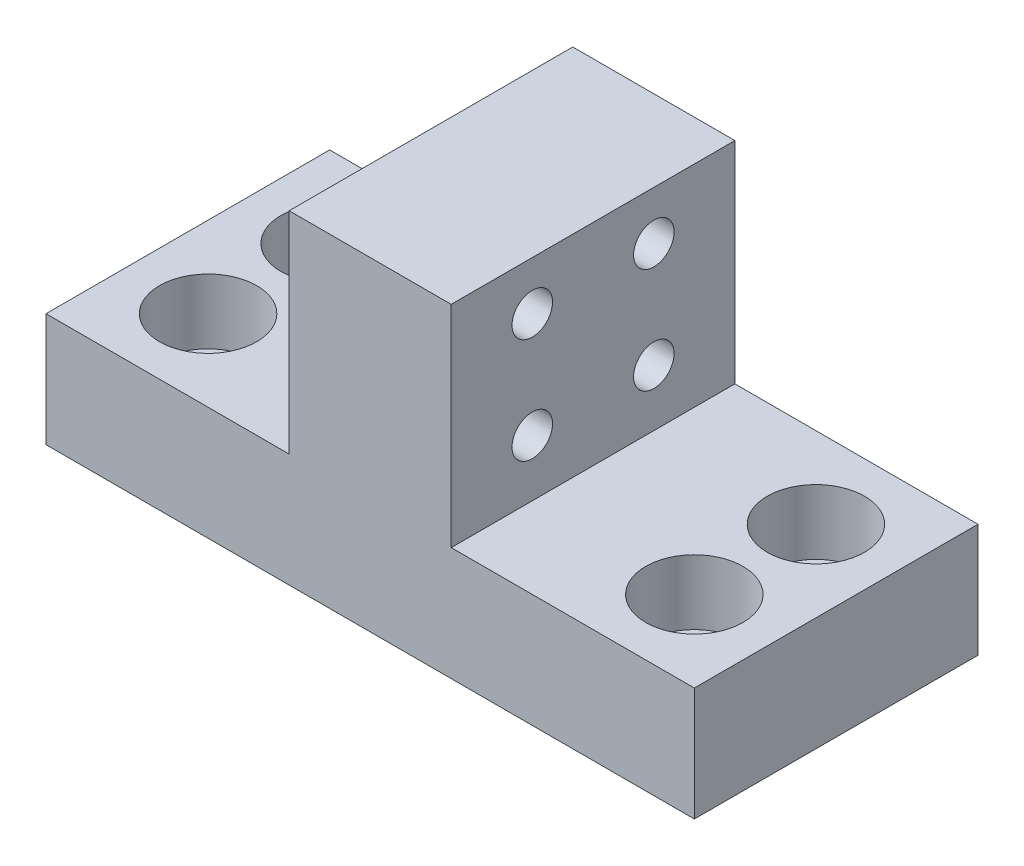
SolidWorks part; units mm, degrees
ref_plane "前视基准面" through (0, 0, 0) normal (0, 0, 1) x (1, 0, 0)
ref_plane "上视基准面" through (0, 0, 0) normal (0, 1, 0) x (1, 0, 0)
ref_plane "右视基准面" through (0, 0, 0) normal (1, 0, 0) x (0, 0, -1)
sketch "草图1" plane through (0, 0, 0) normal (0, 1, 0) x (1, 0, 0)
  line L0 (-40, 17.5) -> (-40, -17.5)
  line L1 (-40, -17.5) -> (40, -17.5)
  line L2 (40, -17.5) -> (40, 17.5)
  line L3 (40, 17.5) -> (-40, 17.5)
  line L4 (0, 0) -> (80, 0) construction
  line L5 (0, 0) -> (0, 15.8626) construction
  point P10 (0, 17.5)
  point P12 (40, 0)
  dimension "D1" = 35
  dimension "D2" = 80
extrude "凸台-拉伸1" add sketch "草图1" along normal blind 14
sketch "草图2" plane through (0, 14, 0) normal (0, 1, 0) x (1, 0, 0)
  line L0 (0, 0) -> (0, 23.1433) construction
  line L1 (0, 0) -> (16.8315, 0) construction
  line L2 (-10, 17.5) -> (-10, -17.5)
  line L3 (40, 17.5) -> (-40, 17.5) construction
  line L4 (-40, -17.5) -> (40, -17.5) construction
  line L5 (10, -17.5) -> (10, 17.5)
  line L6 (10, 17.5) -> (-10, 17.5)
  line L7 (10, -17.5) -> (-10, -17.5)
  point P12 (0, 17.5)
  dimension "D1" = 20
extrude "凸台-拉伸2" add sketch "草图2" along normal blind 26
hole_wizard "M20 六角头螺栓的柱形沉头孔1" positions "草图3" profile "草图4" counterbore size "M20" standard "GB" end condition up to next
sketch "草图3" plane through (0, 14, 0) normal (0, 1, 0) x (1, 0, 0)
  line L0 (-10, 17.5) -> (-40, 17.5) construction
  point P0 (-30, 7.5)
  dimension "D1" = 10
  dimension "D2" = 30
sketch "草图4" plane through (-30, 14, -7.5) normal (1, 0, 0) x (0, 0, 1)
  line L0 (0, 0) -> (0, 14.001)
  line L1 (0, 14.001) -> (3.5, 14.001)
  line L3 (3.5, 14.001) -> (3.5, 8)
  line L4 (3.5, 8) -> (6, 8)
  line L5 (6, 8) -> (6, 0)
  line L7 (6, 0) -> (0, 0)
  line L11 (0, -6.35) -> (0, 107.95) construction
  dimension "通孔孔直径" = 7
  dimension "通孔孔深度" = 14.001
  dimension "柱形沉头孔直径" = 12
  dimension "柱形沉头孔深度" = 8
pattern_linear "阵列(线性)1" count 2 spacing 60 along (1, 0, 0) count 2 spacing 15 along (0, 0, 1) of "M20 六角头螺栓的柱形沉头孔1"
sketch "草图5" plane through (-10, 0, 0) normal (-1, 0, 0) x (0, 0, 1)
  line L0 (-17.5, 0) -> (17.5, 0) construction
  circle A0 centre (-7.5, 21) radius 2.5
  dimension "D1" = 5
  dimension "D2" = 21
  dimension "D3" = 7.5
extrude "切除-拉伸1" cut sketch "草图5" against normal through all
pattern_linear "阵列(线性)2" count 2 spacing 15 along (0, 0, 1) count 2 spacing 13 along (0, 1, 0) of "切除-拉伸1"
